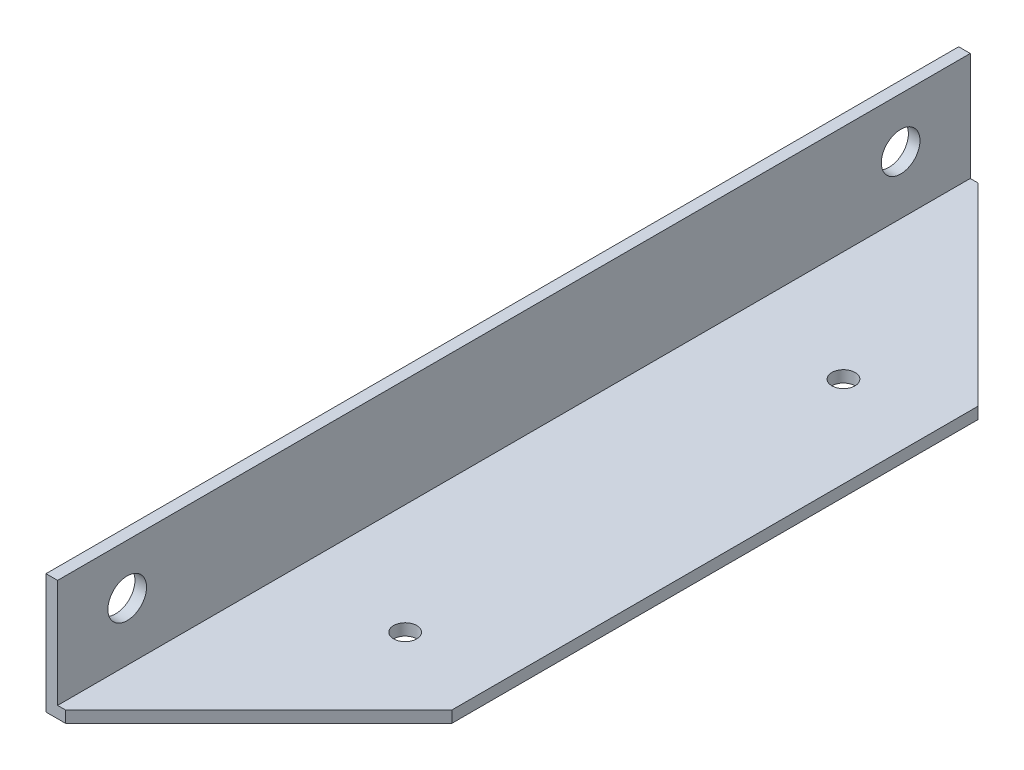
SolidWorks part; units mm, degrees
material "3.0205 (EN-AW 1200)"
ref_plane "Plan de face" through (0, 0, 0) normal (0, 0, 1) x (1, 0, 0)
ref_plane "Plan de dessus" through (0, 0, 0) normal (0, 1, 0) x (1, 0, 0)
ref_plane "Plan de droite" through (0, 0, 0) normal (1, 0, 0) x (0, 0, -1)
sketch "Esquisse1" plane through (0, 0, 0) normal (0, 0, 1) x (1, 0, 0)
  line L0 (0, 15.5) -> (0, 0)
  line L1 (0, 0) -> (27.5, 0)
  dimension "D1" = 15.5
  dimension "D2" = 27.5
extrude "Extru.-Mince1" add sketch "Esquisse1" along normal blind 118 thin thin type one direction reverse wall 1.5
sketch "Esquisse2" plane through (0, 0, 0) normal (-1, 0, 0) x (0, 0, 1)
  line L0 (59, 15.5) -> (59, 0) construction
  line L1 (118, 15.5) -> (0, 15.5) construction
  line L2 (118, 0) -> (0, 0) construction
  line L3 (0, 15.5) -> (0, 0) construction
  circle A0 centre (9, 9) radius 2.5
  circle A1 centre (109, 9) radius 2.5
  dimension "D1" = 100
  dimension "D2" = 5
  dimension "D3" = 9
  dimension "D4" = 9
  dimension "D5" = 6.5
extrude "Enlèv. mat.-Extru.1" cut sketch "Esquisse2" against normal blind 4
sketch "Esquisse3" plane through (0, 0, 0) normal (0, -1, 0) x (1, 0, 0)
  line L0 (27.5, 59) -> (-130, 59) construction
  line L1 (27.5, 118) -> (27.5, 0) construction
  line L2 (-130, 59) -> (15.7716, 30.6649) construction
  line L3 (0, 118) -> (0, 0) construction
  circle A1 centre (15.7716, 30.6649) radius 1.5
  circle A2 centre (15.7716, 87.3351) radius 1.5
  dimension "D1" = 11
  dimension "D3" = 3
  dimension "D2" = 148.5
  dimension "D5" = 130
extrude "Enlèv. mat.-Extru.2" cut sketch "Esquisse3" against normal blind 4
chamfer "Chanfrein1" distance 25 angle 45 2 edges at (27.5, 0.75, 118) (27.5, 0.75, 0)
